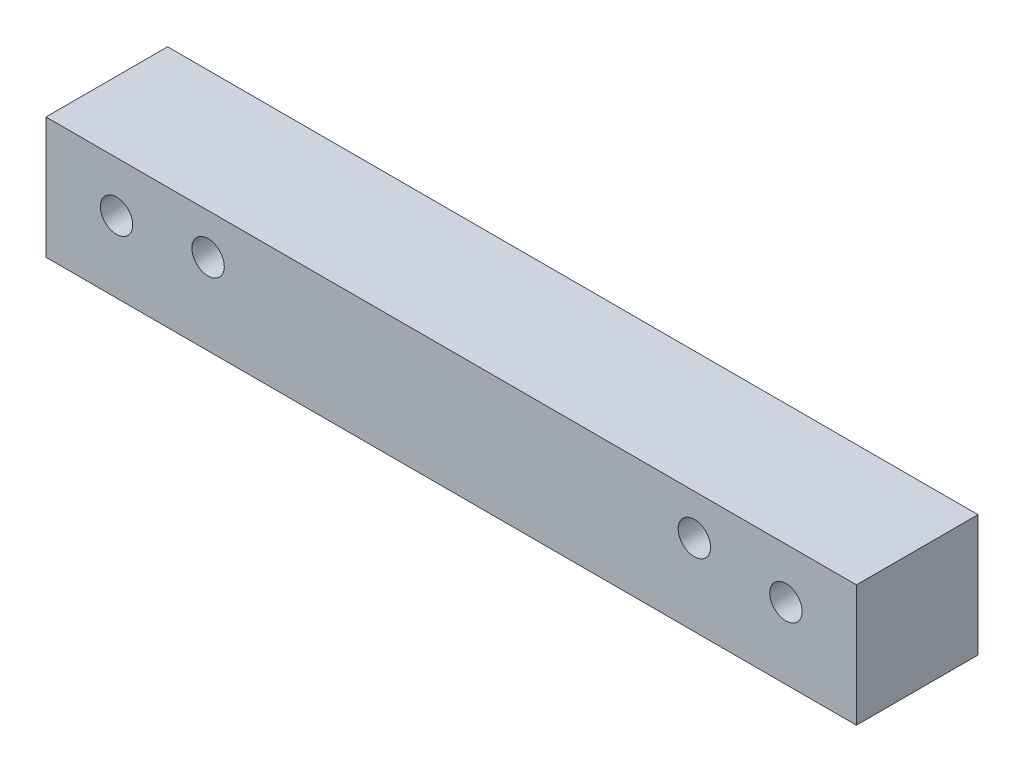
SolidWorks part; units mm, degrees
ref_plane "Front Plane" through (0, 0, 0) normal (0, 0, 1) x (1, 0, 0)
ref_plane "Top Plane" through (0, 0, 0) normal (0, 1, 0) x (1, 0, 0)
ref_plane "Right Plane" through (0, 0, 0) normal (1, 0, 0) x (0, 0, -1)
sketch "Sketch1" plane through (0, 0, 0) normal (0, 1, 0) x (1, 0, 0)
  line L1 (-106.1945, 6.6812) -> (20.8055, 6.6812)
  line L2 (-106.1945, 6.6812) -> (-106.1945, -12.3688)
  line L3 (-106.1945, -12.3688) -> (20.8055, -12.3688)
  line L4 (20.8055, 6.6812) -> (20.8055, -12.3688)
  dimension "D1" = 19.05
  dimension "D2" = 127
extrude "Boss-Extrude1" add sketch "Sketch1" along normal blind 19.05
sketch "Sketch2" plane through (0, 0, 12.3688) normal (0, 0, 1) x (1, 0, 0)
  circle A1 centre (-4.5945, 12.7) radius 2.54
  circle A3 centre (-80.7945, 12.7) radius 2.54
  dimension "D2" = 5.08
extrude "Cut-Extrude1" cut sketch "Sketch2" against normal up to next
sketch "Sketch3" plane through (0, 0, -6.6812) normal (0, 0, -1) x (-1, 0, 0)
  line L0 (-20.8055, 0) -> (106.1945, 0) construction
  line L1 (106.1945, 19.05) -> (106.1945, 0) construction
  circle A0 centre (95.1455, 11.176) radius 2.54
  circle A1 centre (-9.7565, 11.176) radius 2.54
  dimension "D1" = 5.08
  dimension "D2" = 11.176
  dimension "D3" = 11.049
  dimension "D4" = 104.902
extrude "Cut-Extrude2" cut sketch "Sketch3" against normal up to next
